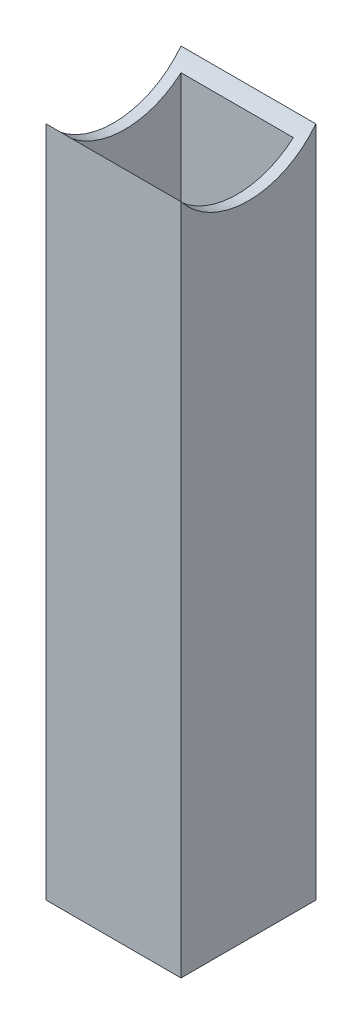
SolidWorks part; units mm, degrees
material "6063-T5"
ref_plane "Front Plane" through (0, 0, 0) normal (0, 0, 1) x (1, 0, 0)
ref_plane "Top Plane" through (0, 0, 0) normal (0, 1, 0) x (1, 0, 0)
ref_plane "Right Plane" through (0, 0, 0) normal (1, 0, 0) x (0, 0, -1)
sketch "Sketch1" plane through (0, 0, 0) normal (1, 0, 0) x (0, 0, -1)
  line L1 (0, 0) -> (38.1, 0)
  line L2 (0, 0) -> (0, 204.7697)
  line L3 (0, 204.7697) -> (38.1, 204.7697)
  line L4 (38.1, 0) -> (38.1, 204.7697)
  circle A0 centre (19.05, 204.7697) radius 24.13
  dimension "D3" = 48.26
  dimension "D1" = 38.1
  dimension "D2" = 204.7697
extrude "Boss-Extrude1" add sketch "Sketch1" along normal blind 38.1 contours A0 L2 L1 L4
sketch "Sketch2" plane through (0, 0, 0) normal (0, -1, 0) x (1, 0, 0)
  line L0 (3.175, -3.175) -> (3.175, -34.925)
  line L1 (3.175, -34.925) -> (34.925, -34.925)
  line L2 (34.925, -34.925) -> (34.925, -3.175)
  line L3 (34.925, -3.175) -> (3.175, -3.175)
  line L4 (0, 0) -> (0, -38.1)
  line L5 (38.1, 0) -> (0, 0)
  line L6 (38.1, -38.1) -> (38.1, 0)
  line L7 (0, -38.1) -> (38.1, -38.1)
  line L8 (0, 0) -> (0, -38.1) construction
  line L9 (38.1, 0) -> (0, 0) construction
  line L10 (38.1, -38.1) -> (38.1, 0) construction
  line L11 (0, -38.1) -> (38.1, -38.1) construction
  dimension "D1" = 0
  dimension "D2" = 3.175
extrude "Cut-Extrude1" cut sketch "Sketch2" against normal through all
